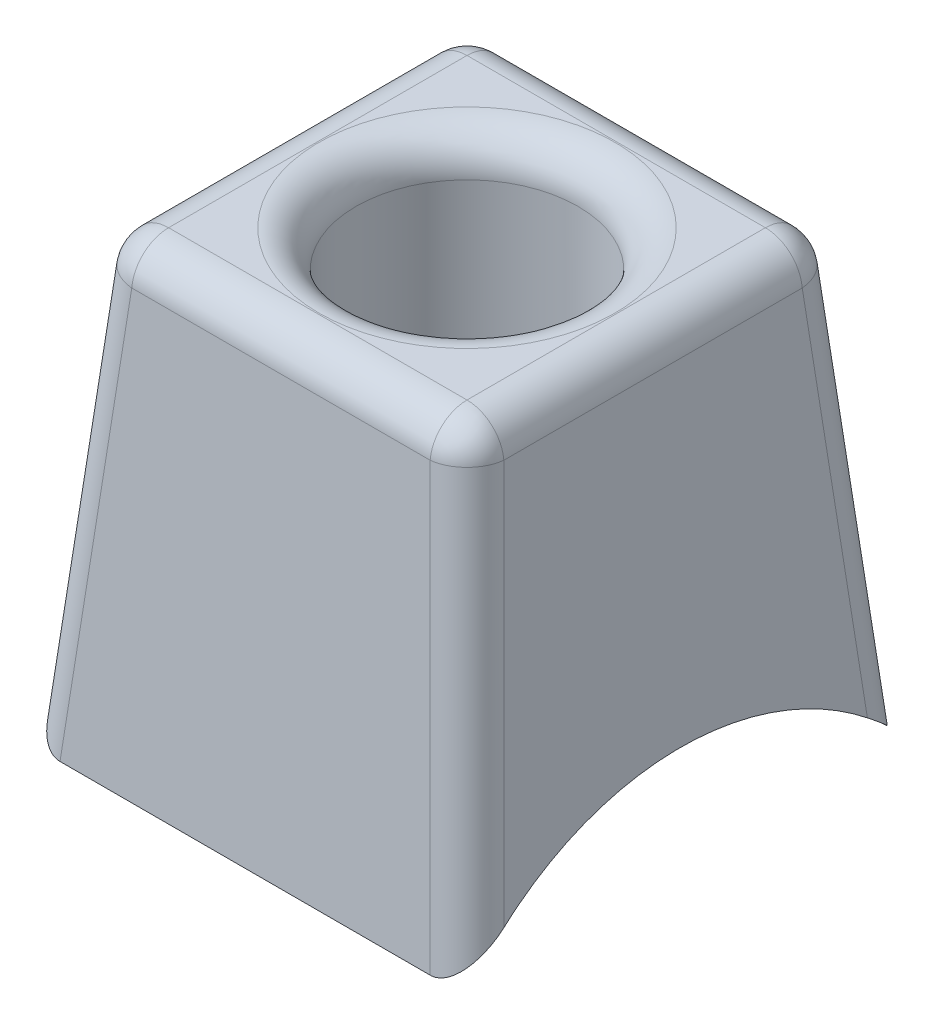
SolidWorks part; units mm, degrees
ref_plane "Front Plane" through (0, 0, 0) normal (0, 0, 1) x (1, 0, 0)
ref_plane "Top Plane" through (0, 0, 0) normal (0, 1, 0) x (1, 0, 0)
ref_plane "Right Plane" through (0, 0, 0) normal (1, 0, 0) x (0, 0, -1)
sketch "Sketch1" plane through (0, 0, 0) normal (0, 1, 0) x (1, 0, 0)
  line L1 (0, 0) -> (-12, 0)
  line L2 (0, 0) -> (0, 12)
  line L3 (0, 12) -> (-12, 12)
  line L4 (-12, 0) -> (-12, 12)
  dimension "D1" = 12
  dimension "D2" = 12
extrude "Boss-Extrude1" add sketch "Sketch1" along normal blind 12 draft 5
sketch "Sketch2" plane through (0, 12, 0) normal (0, 1, 0) x (1, 0, 0)
  line L0 (-10.9501, 6) -> (-1.0499, 6) construction
  line L1 (-10.9501, 10.9501) -> (-10.9501, 1.0499) construction
  line L2 (-1.0499, 1.0499) -> (-1.0499, 10.9501) construction
  line L3 (-6, 10.9501) -> (-6, 1.0499) construction
  line L4 (-1.0499, 10.9501) -> (-10.9501, 10.9501) construction
  line L5 (-10.9501, 1.0499) -> (-1.0499, 1.0499) construction
  circle A0 centre (-6, 6) radius 3
  dimension "D1" = 6
extrude "Cut-Extrude1" cut sketch "Sketch2" against normal through all
fillet "Fillet1" radius 1 9 edges at (-6, 12, -3) (-11.4751, 6, -11.4751) (-0.5249, 6, -11.4751) (-0.5249, 6, -0.5249) (-11.4751, 6, -0.5249) (-6, 12, -10.9501) (-10.9501, 12, -6) (-6, 12, -1.0499) (-1.0499, 12, -6)
sketch "Sketch3" plane through (0, 0, 0) normal (1, 0, 0) x (0, 0, -1)
  line L0 (6, 0) -> (6, 10.2816) construction
  line L1 (11.0038, 0) -> (0.9962, 0) construction
  line L2 (6, 0) -> (6, -8.6425) construction
  circle A0 centre (6, -5.2915) radius 8
  dimension "D1" = 16
extrude "Cut-Extrude2" cut sketch "Sketch3" against normal through all
